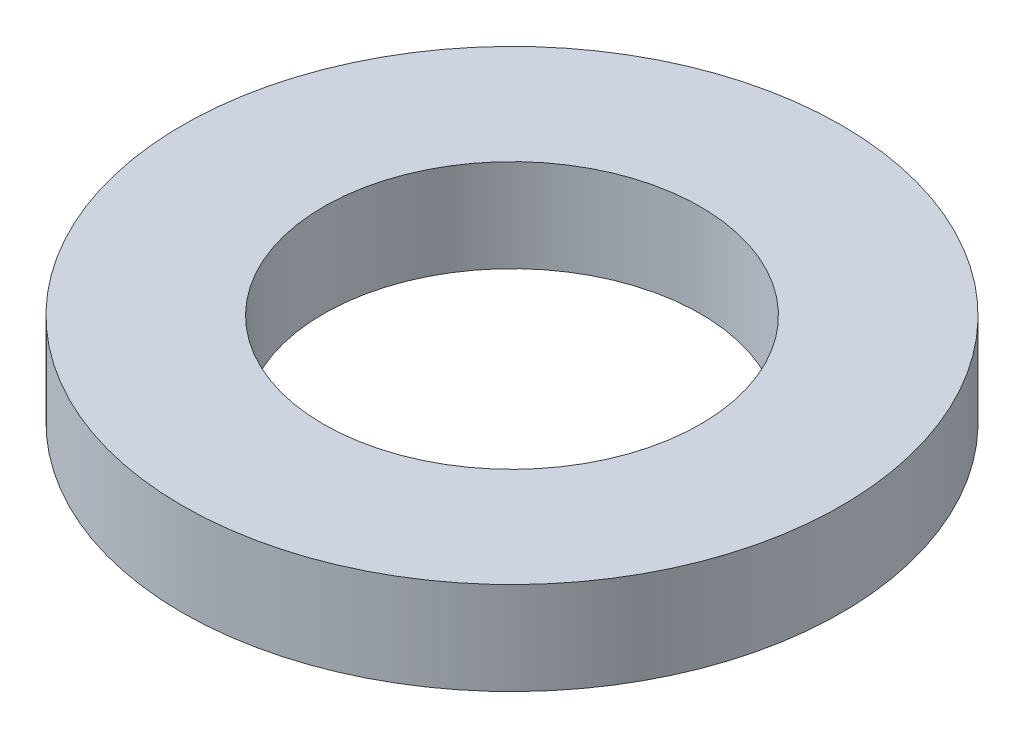
SolidWorks part; units mm, degrees
ref_plane "Front" through (0, 0, 0) normal (0, 0, 1) x (1, 0, 0)
ref_plane "Top" through (0, 0, 0) normal (0, 1, 0) x (1, 0, 0)
ref_plane "Right" through (0, 0, 0) normal (1, 0, 0) x (0, 0, -1)
sketch "Sketch1" plane through (0, 0, 0) normal (0, 1, 0) x (1, 0, 0)
  circle A0 centre (0, 0) radius 5.334
  circle A1 centre (0, 0) radius 3.05
  dimension "D1" = 10.668
  dimension "D2" = 6.1
extrude "Boss-Extrude1" add sketch "Sketch1" along normal blind 1.5
